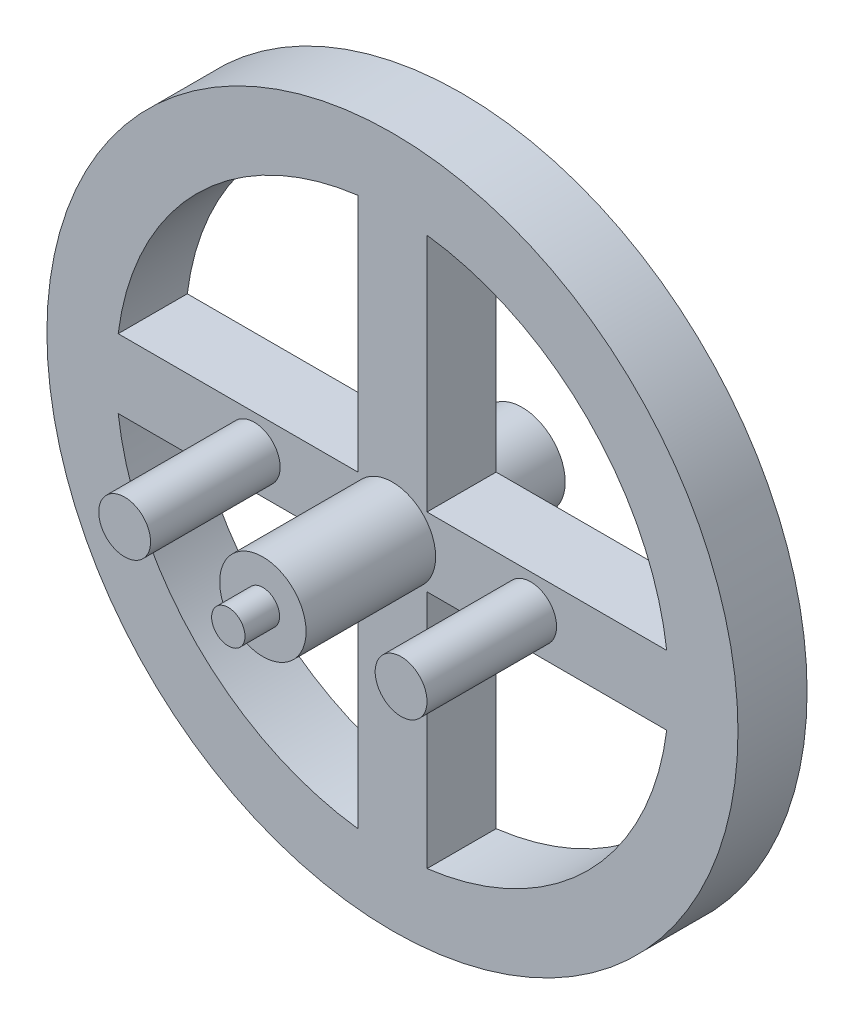
SolidWorks part; units mm, degrees
ref_plane "Plan de face" through (0, 0, 0) normal (0, 0, 1) x (1, 0, 0)
ref_plane "Plan de dessus" through (0, 0, 0) normal (0, 1, 0) x (1, 0, 0)
ref_plane "Plan de droite" through (0, 0, 0) normal (1, 0, 0) x (0, 0, -1)
sketch "Esquisse1" plane through (0, 0, 0) normal (0, 0, 1) x (1, 0, 0)
  line L0 (-15.8745, 2) -> (-2, 2)
  line L1 (-15.8745, -2) -> (-2, -2)
  line L2 (-2, 15.8745) -> (-2, 2)
  line L3 (2, 15.8745) -> (2, 2)
  line L4 (-26.3467, 0) -> (29.742, 0) construction
  line L5 (0, 26.9102) -> (0, -30.6219) construction
  line L6 (-2, -2) -> (-2, -15.8745)
  line L7 (2, 2) -> (15.8745, 2)
  line L8 (2, -2) -> (2, -15.8745)
  line L9 (2, -2) -> (15.8745, -2)
  circle A0 centre (0, 0) radius 20
  arc A1 (-2, 15.8745) -> (-15.8745, 2) centre (0, 0) ccw
  arc A2 (-15.8745, -2) -> (-2, -15.8745) centre (0, 0) ccw
  arc A3 (2, -15.8745) -> (15.8745, -2) centre (0, 0) ccw
  arc A4 (15.8745, 2) -> (2, 15.8745) centre (0, 0) ccw
  dimension "D1" = 40
  dimension "D6" = 32
  dimension "D2" = 2
  dimension "D3" = 2
  dimension "D4" = 2
  dimension "D5" = 2
extrude "Boss.-Extru.1" add sketch "Esquisse1" along normal blind 4
sketch "Esquisse2" plane through (0, 0, 4) normal (0, 0, 1) x (1, 0, 0)
  circle A0 centre (0, 0) radius 2.5
  dimension "D1" = 5
extrude "Boss.-Extru.2" add sketch "Esquisse2" along normal mid plane 15
sketch "Esquisse3" plane through (0, 0, 11.5) normal (0, 0, 1) x (1, 0, 0)
  circle A0 centre (0, 0) radius 0.9665
extrude "Boss.-Extru.3" add sketch "Esquisse3" along normal blind 2
sketch "Esquisse4" plane through (0, 0, 4) normal (0, 0, 1) x (1, 0, 0)
  circle A0 centre (8, 0) radius 1.5
  circle A1 centre (-8, 0) radius 1.5
  dimension "D1" = 3
  dimension "D2" = 3
  dimension "D3" = 8
  dimension "D4" = 8
extrude "Boss.-Extru.4" add sketch "Esquisse4" along normal blind 7.5
